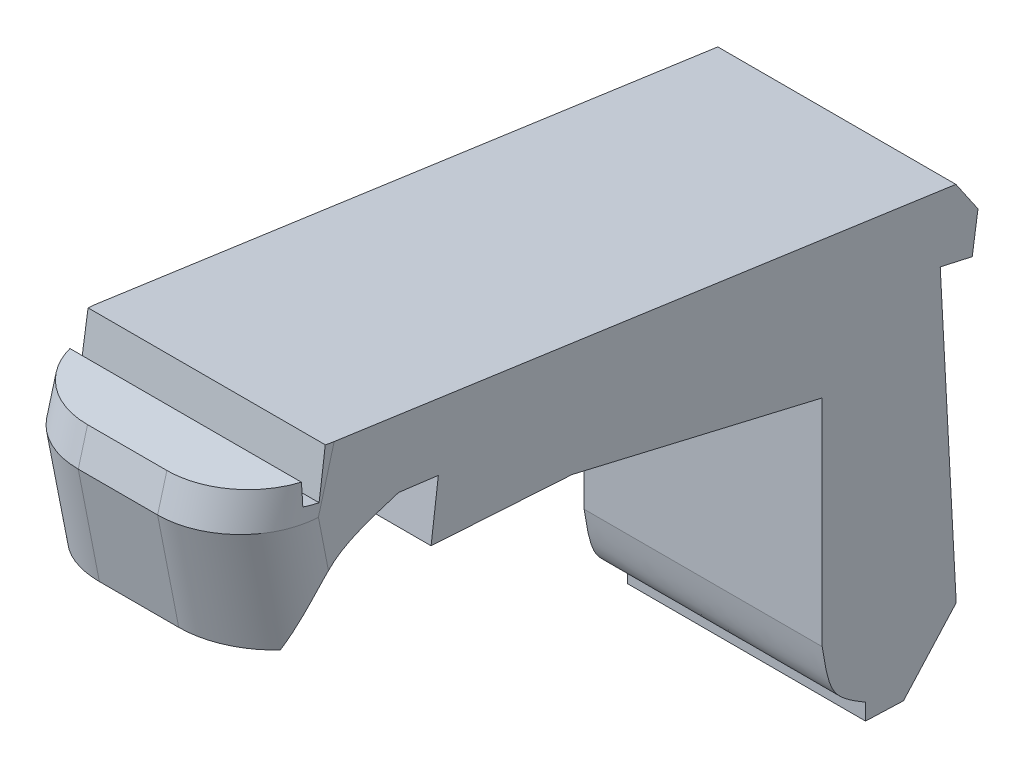
SolidWorks part; units mm, degrees
ref_plane "Front Plane" through (0, 0, 0) normal (0, 0, 1) x (1, 0, 0)
ref_plane "Top Plane" through (0, 0, 0) normal (0, 1, 0) x (1, 0, 0)
ref_plane "Right Plane" through (0, 0, 0) normal (1, 0, 0) x (0, 0, -1)
sketch "Sketch1" plane through (0, 0, 0) normal (1, 0, 0) x (0, 0, -1)
  line L20 (711.5482, -160.15) -> (669.0633, -98.1665)
  line L21 (669.0633, -98.1665) -> (-541.134, 73.3228)
  line L22 (-541.134, 73.3228) -> (-553.825, -16.2376)
  line L23 (-553.825, -16.2376) -> (-581.4926, -11.3958)
  line L24 (-581.4926, -11.3958) -> (-581.4926, 28.6111)
  line L25 (-581.4926, 28.6111) -> (-693.7698, 31.1922)
  line L26 (-693.7698, 31.1922) -> (-711.5482, -33.9108)
  line L27 (-711.5482, -33.9108) -> (-671.0382, -241.1997)
  line L28 (-671.0382, -241.1997) -> (-601.6759, -250.5291)
  line L29 (-401.0435, -75.5458) -> (-324.8088, -85.2229)
  line L30 (-324.8088, -85.2229) -> (-338.7979, -195.4271)
  line L31 (-338.7979, -195.4271) -> (-67.7595, -212.3366)
  line L32 (-67.7595, -212.3366) -> (412.2404, -324.9819)
  line L33 (412.2404, -324.9819) -> (412.2404, -738.5764)
  line L34 (495.5919, -872.7207) -> (495.5919, -904.1743)
  line L35 (495.5919, -904.1743) -> (568.4517, -906.7982)
  line L36 (568.4517, -906.7982) -> (669.7267, -794.2759)
  line L37 (669.7267, -794.2759) -> (638.9799, -220.5)
  line L38 (638.9799, -220.5) -> (700.4735, -234.2026)
  line L39 (700.4735, -234.2026) -> (711.5482, -160.15)
  spline S2 degree 2 poles (-601.6759, -250.5291) (-541.134, -117.433) (-401.0435, -75.5458) knots 0 0 0 1 1 1 weights 1 2.24602 1
  spline S3 degree 2 poles (412.2404, -738.5764) (426.2823, -832.1277) (495.5919, -872.7207) knots 0 0 0 1 1 1 weights 1 2.187228 1
extrude "Boss-Extrude1" add sketch "Sketch1" along normal blind 457.2
fillet "Fillet1" radius 152.4 4 edges at (0, -137.5553, 691.2932) (0, -1.3593, 702.659) (457.2, -137.5553, 691.2932) (457.2, -1.3593, 702.659)
